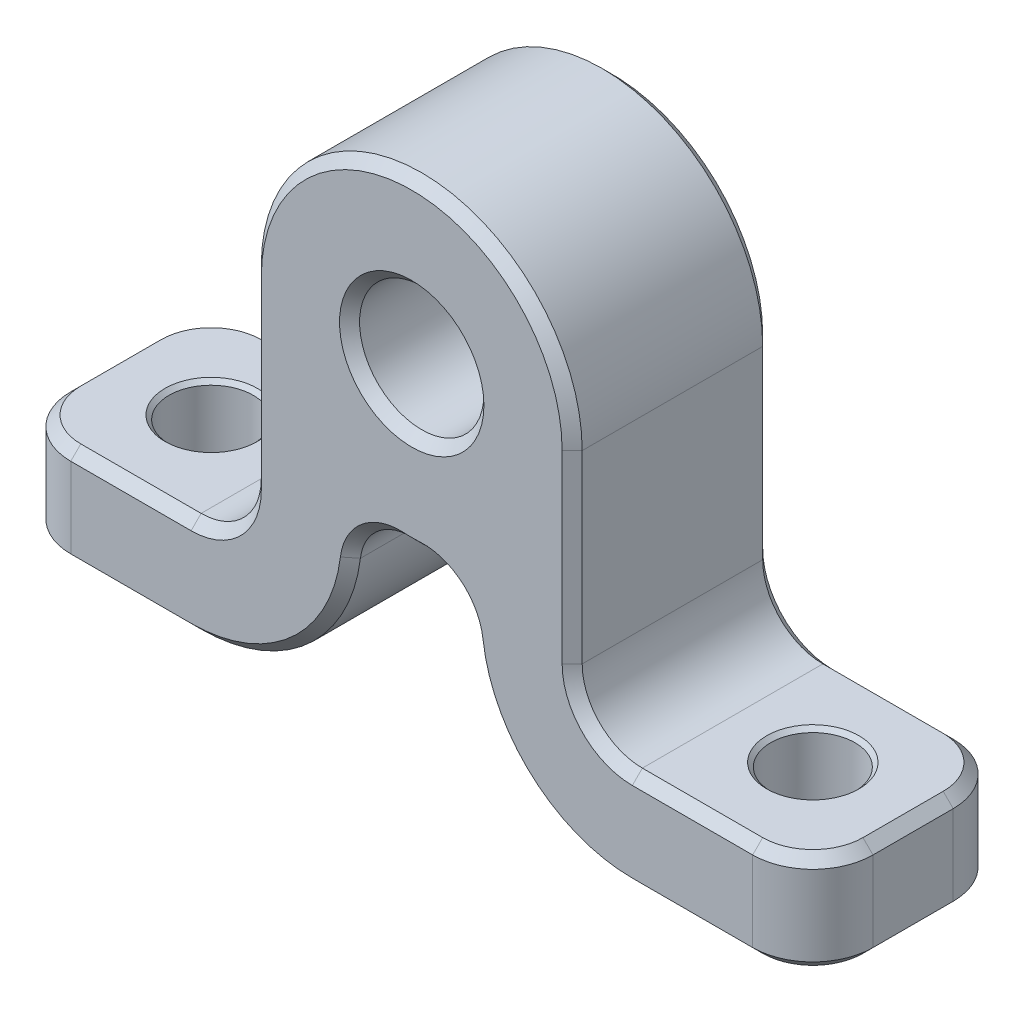
SolidWorks part; units mm, degrees
material "镀铬不锈钢"
ref_plane "前视基准面" through (0, 0, 0) normal (0, 0, 1) x (1, 0, 0)
ref_plane "上视基准面" through (0, 0, 0) normal (0, 1, 0) x (1, 0, 0)
ref_plane "右视基准面" through (0, 0, 0) normal (1, 0, 0) x (0, 0, -1)
sketch "草图1" plane through (0, 0, 0) normal (0, 0, 1) x (1, 0, 0)
  line L1 (-20, -17.21) -> (20, -17.21)
  line L2 (-20, -17.21) -> (-20, -12.21)
  line L3 (-20, -12.21) -> (20, -12.21)
  line L4 (20, -17.21) -> (20, -12.21)
  line L5 (-20, -17.21) -> (20, -12.21) construction
  line L6 (-20, -12.21) -> (20, -17.21) construction
  circle A0 centre (0, 0) radius 3.1
  circle A1 centre (0, 0) radius 8
  point P4 (0, -14.71)
  point P9 (0, -17.21)
  dimension "D1" = 6.2
  dimension "D2" = 16
  dimension "D3" = 40
  dimension "D4" = 5
  dimension "D5" = 12.21
extrude "凸台-拉伸1" add sketch "草图1" along normal mid plane 10 contours L3 A1 A0 | L3 A1 | A1 L1 L4 L3 | A1 L3 L2 L1
chamfer "倒角7" distance 0.5 angle 45 2 edges at (3.1, 0, 5) (3.1, 0, -5)
sketch "Sketch1" plane through (0, 0, -5) normal (0, 0, -1) x (-1, 0, 0)
  line L0 (-8, 0) -> (-8, -12.21)
  line L1 (20, -12.21) -> (-20, -12.21) construction
  line L2 (-8, -12.21) -> (8, -12.21)
  line L3 (8, -12.21) -> (8, 0)
  circle A1 centre (0, 0) radius 8
  circle A2 centre (0, 0) radius 8
  line M4 (20, -12.21) -> (-20, -12.21)
  dimension "D1" = 0
extrude "Extrude1" add sketch "Sketch1" against normal up to surface (10 mm away) contours A2 L0 L3 M4 up to face at (3.6, 0, 5)
fillet "Fillet1" radius 3 2 edges at (-8, -12.21, 0) (8, -12.21, 0)
sketch "Sketch2" plane through (0, 0, -5) normal (0, 0, -1) x (-1, 0, 0)
  line L0 (-3, -7.4162) -> (-3, -17.21)
  line L1 (20, -17.21) -> (-20, -17.21) construction
  line L2 (-3, -17.21) -> (3, -17.21)
  line L3 (3, -17.21) -> (3, -7.4162)
  line L4 (-8, 0) -> (-8, -9.21) construction
  circle A0 centre (0, 0) radius 8
  line M10 (-20, -17.21) -> (20, -17.21)
  dimension "D1" = 16
  dimension "D2" = 5
extrude "Extrude2" cut sketch "Sketch2" against normal blind 4.5 contours A0 L0 L3 M10
mirror "Mirror1" about plane through (0, 0, 0) normal (0, 0, 1) of "Extrude2"
fillet "Fillet2" radius 8 4 edges at (-3, -17.21, 2.75) (3, -17.21, 2.75) (-3, -17.21, -2.75) (3, -17.21, -2.75)
sketch "Sketch3" plane through (0, -12.21, 0) normal (0, 1, 0) x (1, 0, 0)
  line L0 (0, 0) -> (0, -5) construction
  line L1 (-8, -5) -> (8, -5) construction
  circle A0 centre (15, 0) radius 2.1
  circle A1 centre (-15, 0) radius 2.1
  dimension "D1" = 30
  dimension "D2" = 4.2
extrude "Extrude3" cut sketch "Sketch3" against normal through all
chamfer "Chamfer2" distance 0.2 angle 45 4 edges at (-15, -12.21, -2.1) (-15, -17.21, -2.1) (15, -12.21, 2.1) (15, -17.21, 2.1)
sketch "Sketch4" plane through (0, 0, -0.5) normal (0, 0, -1) x (-1, 0, 0)
  line L1 (-11, -17.21) -> (11, -17.21)
  line L2 (-11, -17.21) -> (11, -17.21)
  line L5 (-3, -7.4162) -> (-3, -9.21)
  line L11 (-3, -7.4162) -> (-3, -9.21)
  line L13 (3, -9.21) -> (3, -7.4162)
  line L14 (3, -9.21) -> (3, -7.4162)
  arc A3 (-3, -7.4162) -> (3, -7.4162) centre (0, 0) ccw
  arc A4 (-11, -17.21) -> (-3, -9.21) centre (-11, -9.21) ccw
  arc A5 (3, -9.21) -> (11, -17.21) centre (11, -9.21) ccw
  arc A6 (-3, -7.4162) -> (3, -7.4162) centre (0, 0) ccw
  arc A7 (-11, -17.21) -> (-3, -9.21) centre (-11, -9.21) ccw
  arc A8 (3, -9.21) -> (11, -17.21) centre (11, -9.21) ccw
  dimension "D1" = 0
extrude "Extrude4" cut sketch "Sketch4" against normal through all
fillet "Fillet3" radius 2.5 2 edges at (-3, -7.4162, 0) (3, -7.4162, 0)
fillet "Fillet4" radius 3 4 edges at (-20, -14.71, -5) (-20, -14.71, 5) (20, -14.71, -5) (20, -14.71, 5)
chamfer "Chamfer4" distance 0.5 angle 45 40 edges at (14, -12.21, -5) (14, -12.21, 5) (-14, -12.21, -5) (-14, -12.21, 5) (8.8787, -11.3313, 5) (8.8787, -11.3313, -5) (-8.8787, -11.3313, 5) (-8.8787, -11.3313, -5) (8, -4.605, 5) (8, -4.605, -5) (-8, -4.605, -5) (-8, -4.605, 5) (0, 8, 5) (0, 8, -5) (19.1213, -12.21, -4.1213) (-19.1213, -12.21, -4.1213) (20, -12.21, 0) (-20, -12.21, 0) (19.1213, -12.21, 4.1213) (-19.1213, -12.21, 4.1213) (0, -8, 5) (0, -8, -5) (5.6975, -15.2002, 5) (5.6975, -15.2002, -5) (-5.6975, -15.2002, -5) (-5.6975, -15.2002, 5) (14, -17.21, -5) (-14, -17.21, -5) (19.1213, -17.21, -4.1213) (-19.1213, -17.21, -4.1213) (20, -17.21, 0) (-20, -17.21, 0) (19.1213, -17.21, 4.1213) (-19.1213, -17.21, 4.1213) (14, -17.21, 5) (-14, -17.21, 5) (2.1825, -8.5673, 5) (2.1825, -8.5673, -5) (-2.1825, -8.5673, 5) (-2.1825, -8.5673, -5)
